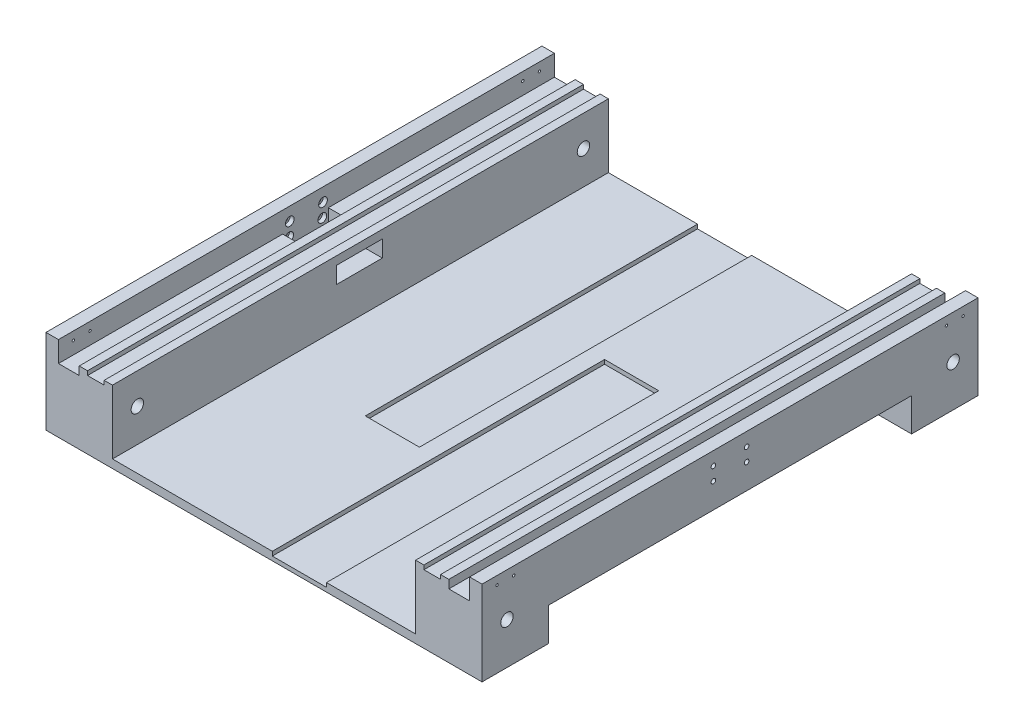
SolidWorks part; units mm, degrees
ref_plane "Front Plane" through (0, 0, 0) normal (0, 0, 1) x (1, 0, 0)
ref_plane "Top Plane" through (0, 0, 0) normal (0, 1, 0) x (1, 0, 0)
ref_plane "Right Plane" through (0, 0, 0) normal (1, 0, 0) x (0, 0, -1)
sketch "Sketch1" plane through (0, 0, 0) normal (0, 0, 1) x (1, 0, 0)
  line L0 (0, 0) -> (0, 95)
  line L1 (0, 95) -> (20, 95)
  line L2 (20, 95) -> (20, 75)
  line L3 (20, 75) -> (40, 75)
  line L4 (40, 75) -> (40, 80)
  line L5 (40, 80) -> (50, 80)
  line L6 (50, 80) -> (50, 75)
  line L7 (50, 75) -> (70, 75)
  line L8 (70, 75) -> (70, 80)
  line L9 (70, 80) -> (80, 80)
  line L10 (80, 80) -> (80, 15)
  line L11 (80, 15) -> (445, 15)
  line L23 (237.9167, 0) -> (0, 0)
  line L24 (262.5, 146.857) -> (262.5, -30.5268)
  line L25 (287.0833, 0) -> (525, 0)
  line L26 (445, 80) -> (445, 15)
  line L27 (455, 80) -> (445, 80)
  line L28 (455, 75) -> (455, 80)
  line L29 (475, 75) -> (455, 75)
  line L30 (485, 80) -> (475, 80)
  line L31 (485, 75) -> (485, 80)
  line L32 (505, 75) -> (485, 75)
  line L33 (505, 95) -> (505, 75)
  line L34 (525, 95) -> (505, 95)
  line L35 (525, 0) -> (525, 95)
  line L36 (475, 75) -> (475, 80)
  line L37 (237.9167, 0) -> (287.0833, 0)
  point P19 (262.5, 15)
  dimension "D1" = 10
  dimension "D2" = 10
  dimension "D3" = 182.5
  dimension "D4" = 20
  dimension "D5" = 20
  dimension "D6" = 20
  dimension "D7" = 20
  dimension "D8" = 5
  dimension "D9" = 5
  dimension "D10" = 65
  dimension "D11" = 80
  dimension "D12" = 95
extrude "Boss-Extrude1" add sketch "Sketch1" along normal blind 597.1 contours L23 L37 L24 L11 L10 L9 L8 L7 L6 L5 L4 L3 L2 L1 L0 | L24 L37 L25 L35 L34 L33 L32 L31 L30 L36 L29 L28 L27 L26 L11
sketch "Sketch2" plane through (0, 15, 0) normal (0, 1, 0) x (1, 0, 0)
  line L0 (80, 0) -> (445, 0) construction
  line L1 (187.3, 0) -> (252.5, 0)
  line L2 (187.3, 0) -> (187.3, -400)
  line L3 (187.3, -400) -> (252.5, -400)
  line L4 (252.5, 0) -> (252.5, -400)
  line L5 (80, -597.1) -> (445, -597.1) construction
  line L6 (272.5, -597.1) -> (337.7, -597.1)
  line L7 (272.5, -597.1) -> (272.5, -197.1)
  line L8 (272.5, -197.1) -> (337.7, -197.1)
  line L9 (337.7, -597.1) -> (337.7, -197.1)
  line L10 (445, -597.1) -> (445, 0) construction
  dimension "D1" = 400
  dimension "D2" = 400
  dimension "D3" = 65.2
  dimension "D4" = 65.2
  dimension "D5" = 20
  dimension "D6" = 107.3
extrude "Cut-Extrude1" cut sketch "Sketch2" against normal through all
sketch "Sketch3" plane through (0, 15, 0) normal (0, 1, 0) x (1, 0, 0)
  line L1 (80, 0) -> (445, 0)
  line L2 (80, 0) -> (80, -597.1)
  line L3 (80, -597.1) -> (445, -597.1)
  line L4 (445, 0) -> (445, -597.1)
  line L5 (187.3, 0) -> (252.5, 0)
  line L6 (187.3, 0) -> (187.3, -400)
  line L7 (187.3, -400) -> (252.5, -400)
  line L8 (252.5, 0) -> (252.5, -400)
  line L9 (272.5, -197.1) -> (337.7, -197.1)
  line L10 (272.5, -197.1) -> (272.5, -597.1)
  line L11 (272.5, -597.1) -> (337.7, -597.1)
  line L12 (337.7, -197.1) -> (337.7, -597.1)
  line M1 (187.3, -400) -> (187.3, 0)
  line M2 (187.3, 0) -> (80, 0)
  line M3 (80, 0) -> (80, -597.1)
  line M4 (80, -597.1) -> (272.5, -597.1)
  line M5 (272.5, -597.1) -> (272.5, -197.1)
  line M6 (272.5, -197.1) -> (337.7, -197.1)
  line M7 (337.7, -197.1) -> (337.7, -597.1)
  line M8 (337.7, -597.1) -> (445, -597.1)
  line M9 (445, -597.1) -> (445, 0)
  line M10 (445, 0) -> (252.5, 0)
  line M11 (252.5, 0) -> (252.5, -400)
  line M12 (252.5, -400) -> (187.3, -400)
extrude "Boss-Extrude2" add sketch "Sketch3" along normal blind 8 contours M12 M1 M2 M3 M4 M5 M6 M7 M8 M9 M10 M11
sketch "Sketch4" plane through (0, 0, 0) normal (0, -1, 0) x (1, 0, 0)
  line L1 (0, 597.1) -> (525, 597.1)
  line L2 (0, 597.1) -> (0, 0)
  line L3 (0, 0) -> (525, 0)
  line L4 (525, 597.1) -> (525, 0)
extrude "Boss-Extrude3" add sketch "Sketch4" along normal blind 7
sketch "Sketch5" plane through (0, 23, 0) normal (0, 1, 0) x (1, 0, 0)
  line L1 (80, 0) -> (445, 0)
  line L2 (80, 0) -> (80, -597.1)
  line L3 (80, -597.1) -> (445, -597.1)
  line L4 (445, 0) -> (445, -597.1)
extrude "Cut-Extrude2" cut sketch "Sketch5" against normal blind 10
sketch "Sketch6" plane through (525, 0, 0) normal (1, 0, 0) x (0, 0, -1)
  line L0 (-597.1, 95) -> (0, 95) construction
  line L1 (-324.55, 95) -> (-272.55, 95)
  line L2 (-324.55, 95) -> (-324.55, 55)
  line L3 (-324.55, 55) -> (-272.55, 55)
  line L4 (-272.55, 95) -> (-272.55, 55)
  line L6 (-597.1, -7) -> (-597.1, 95) construction
  circle A0 centre (-318.55, 79) radius 2.125
  circle A1 centre (-278.55, 79) radius 2.125
  circle A2 centre (-278.55, 63) radius 2.125
  circle A3 centre (-318.55, 63) radius 2.125
  circle A4 centre (-318.55, 79) radius 2.125
  circle A5 centre (-278.55, 79) radius 2.125
  circle A6 centre (-278.55, 63) radius 2.125
  circle A7 centre (-318.55, 63) radius 2.125
  dimension "D4" = 4.25
  dimension "D1" = 52
  dimension "D2" = 40
  dimension "D3" = 272.55
  dimension "D5" = 40
  dimension "D6" = 40
  dimension "D7" = 16
  dimension "D8" = 16
  dimension "D9" = 6
  dimension "D10" = 8
extrude "Cut-Extrude3" cut sketch "Sketch6" against normal up to next contours A0 | A3 | A2 | A1
cosmetic thread "Cosmetic Thread5" parameters "D2"=5.5
cosmetic thread "Cosmetic Thread6" parameters "D2"=5.5
cosmetic thread "Cosmetic Thread7" parameters "D2"=5.5
cosmetic thread "Cosmetic Thread8" parameters "D2"=5.5
sketch "Sketch7" plane through (0, 75, 0) normal (0, 1, 0) x (1, 0, 0)
  line L1 (485, 0) -> (505, 0)
  line L2 (485, 0) -> (485, -597.1)
  line L3 (485, -597.1) -> (505, -597.1)
  line L4 (505, 0) -> (505, -597.1)
extrude "Cut-Extrude4" cut sketch "Sketch7" against normal blind 5
sketch "Sketch8" plane through (445, 0, 0) normal (-1, 0, 0) x (0, 0, 1)
  line L0 (597.1, 80) -> (0, 80) construction
  line L1 (269.8676, 50) -> (324.923, 50)
  line L2 (269.8676, 50) -> (269.8676, 70)
  line L3 (269.8676, 70) -> (324.923, 70)
  line L4 (324.923, 50) -> (324.923, 70)
  dimension "D1" = 20
  dimension "D2" = 55.0555
  dimension "D3" = 10
extrude "Cut-Extrude6" cut sketch "Sketch8" against normal blind 60
sketch "Sketch13" plane through (0, 50, 0) normal (0, 1, 0) x (1, 0, 0)
  line L0 (445, -269.8676) -> (445, -324.923) construction
  line L1 (445, -290.3007) -> (485, -290.3007)
  line L2 (445, -290.3007) -> (445, -305.3007)
  line L3 (445, -305.3007) -> (485, -305.3007)
  line L4 (485, -290.3007) -> (485, -305.3007)
  dimension "D1" = 15
  dimension "D2" = 40
extrude "Boss-Extrude4" add sketch "Sketch13" along normal up to next
sketch "Sketch14" plane through (0, 75, 0) normal (0, 1, 0) x (1, 0, 0)
  line L1 (20, 0) -> (40, 0)
  line L2 (20, 0) -> (20, -597.1)
  line L3 (20, -597.1) -> (40, -597.1)
  line L4 (40, 0) -> (40, -597.1)
extrude "Cut-Extrude7" cut sketch "Sketch14" against normal blind 5
sketch "Sketch15" plane through (0, 0, 0) normal (-1, 0, 0) x (0, 0, 1)
  line L0 (597.1, 95) -> (0, 95) construction
  line L1 (10, 95) -> (37, 95)
  line L2 (10, 95) -> (10, 49.6)
  line L3 (10, 49.6) -> (37, 49.6)
  line L4 (37, 95) -> (37, 49.6)
  line L5 (0, -7) -> (0, 95) construction
  line L10 (298.55, -7) -> (298.55, 95)
  line L11 (597.1, -7) -> (0, -7) construction
  line L12 (587.1, 49.6) -> (560.1, 49.6)
  line L13 (587.1, 95) -> (560.1, 95)
  line L14 (587.1, 95) -> (587.1, 49.6)
  line L15 (560.1, 95) -> (560.1, 49.6)
  circle A0 centre (13.5, 82.3) radius 1.33
  circle A1 centre (33.5, 82.3) radius 1.33
  circle A2 centre (33.5, 62.3) radius 1.33
  circle A3 centre (13.5, 62.3) radius 1.33
  circle A4 centre (563.6, 62.3) radius 1.33
  circle A5 centre (563.6, 82.3) radius 1.33
  circle A6 centre (583.6, 82.3) radius 1.33
  circle A7 centre (583.6, 62.3) radius 1.33
  circle A8 centre (13.5, 82.3) radius 1.33
  circle A9 centre (33.5, 82.3) radius 1.33
  circle A10 centre (33.5, 62.3) radius 1.33
  circle A11 centre (13.5, 62.3) radius 1.33
  dimension "D2" = 2.66
  dimension "D1" = 10
  dimension "D3" = 45.4
  dimension "D4" = 27
  dimension "D5" = 20
  dimension "D6" = 20
  dimension "D7" = 20
  dimension "D8" = 20
  dimension "D9" = 3.5
  dimension "D10" = 12.7
extrude "Cut-Extrude8" cut sketch "Sketch15" against normal up to next contours A0 | A1 | A3 | A2 | A5 | A7 | A4 | A6
cosmetic thread "Cosmetic Thread9" parameters "D2"=3.2
cosmetic thread "Cosmetic Thread10" parameters "D2"=3.2
cosmetic thread "Cosmetic Thread11" parameters "D2"=3.2
cosmetic thread "Cosmetic Thread12" parameters "D2"=3.2
cosmetic thread "Cosmetic Thread13" parameters "D2"=3.2
cosmetic thread "Cosmetic Thread14" parameters "D2"=3.2
cosmetic thread "Cosmetic Thread15" parameters "D2"=3.2
cosmetic thread "Cosmetic Thread16" parameters "D2"=3.2
sketch "Sketch16" plane through (80, 0, 0) normal (1, 0, 0) x (0, 0, -1)
  line L0 (-597.1, 80) -> (-597.1, 13) construction
  line L1 (-592.1, 70) -> (-557.1, 70)
  line L2 (-592.1, 70) -> (-592.1, 55)
  line L3 (-592.1, 55) -> (-557.1, 55)
  line L4 (-557.1, 70) -> (-557.1, 55)
  line L5 (-597.1, 80) -> (0, 80) construction
  line L6 (0, 80) -> (0, 13) construction
  line L7 (-40, 55) -> (-5, 55)
  line L8 (-40, 55) -> (-40, 70)
  line L9 (-40, 70) -> (-5, 70)
  line L10 (-5, 55) -> (-5, 70)
  dimension "D1" = 5
  dimension "D2" = 15
  dimension "D3" = 10
  dimension "D4" = 35
  dimension "D5" = 10
  dimension "D6" = 5
  dimension "D7" = 35
  dimension "D8" = 15
extrude "Cut-Extrude9" cut sketch "Sketch16" against normal blind 60
sketch "Sketch17" plane through (0, -7, 0) normal (0, -1, 0) x (1, 0, 0)
  line L0 (525, 0) -> (525, 597.1) construction
  line L1 (465, 373.55) -> (525, 373.55)
  line L2 (465, 373.55) -> (465, 223.55)
  line L3 (465, 223.55) -> (525, 223.55)
  line L4 (525, 373.55) -> (525, 223.55)
  line L5 (525, 597.1) -> (0, 597.1) construction
  dimension "D1" = 150
  dimension "D2" = 223.55
  dimension "D3" = 60
extrude "Cut-Extrude10" cut sketch "Sketch17" against normal blind 40
sketch "Sketch18" plane through (0, 13, 0) normal (0, 1, 0) x (1, 0, 0)
  line L1 (427, -286.05) -> (415, -286.05)
  line L2 (427, -286.05) -> (427, -302.05)
  line L3 (427, -302.05) -> (415, -302.05)
  line L4 (415, -286.05) -> (415, -302.05)
  line L5 (417, -286.05) -> (425, -286.05)
  line L6 (445, 0) -> (252.5, 0) construction
  line L7 (417, -286.05) -> (417, -279.05)
  line L8 (445, -597.1) -> (445, 0) construction
  line L9 (417, -279.05) -> (425, -279.05)
  line L10 (425, -286.05) -> (425, -279.05)
  line L11 (417, -302.05) -> (425, -302.05)
  line L12 (417, -302.05) -> (417, -309.05)
  line L13 (417, -309.05) -> (425, -309.05)
  line L14 (425, -302.05) -> (425, -309.05)
  dimension "D1" = 12
  dimension "D2" = 16
  dimension "D3" = 286.05
  dimension "D4" = 30
  dimension "D5" = 8
  dimension "D6" = 7
  dimension "D7" = 2
  dimension "D8" = 8
  dimension "D9" = 7
  dimension "D10" = 2
extrude "Cut-Extrude11" cut sketch "Sketch18" against normal through all contours L1 L4 L3 L2
sketch "Sketch19" plane through (0, 13, 0) normal (0, 1, 0) x (1, 0, 0)
  line L0 (427, -286.05) -> (415, -286.05) construction
  line L1 (417, -286.05) -> (425, -286.05)
  line L2 (417, -286.05) -> (417, -279.05)
  line L3 (417, -279.05) -> (425, -279.05)
  line L4 (425, -286.05) -> (425, -279.05)
  line L5 (427, -302.05) -> (415, -302.05) construction
  line L6 (417, -302.05) -> (425, -302.05)
  line L7 (417, -302.05) -> (417, -309.05)
  line L8 (417, -309.05) -> (425, -309.05)
  line L9 (425, -302.05) -> (425, -309.05)
  line L10 (415, -286.05) -> (415, -302.05) construction
  dimension "D1" = 8
  dimension "D2" = 8
  dimension "D3" = 7
  dimension "D4" = 7
  dimension "D5" = 2
  dimension "D6" = 2
extrude "Cut-Extrude12" cut sketch "Sketch19" against normal blind 10
sketch "Sketch20" plane through (525, 0, 0) normal (1, 0, 0) x (0, 0, -1)
  circle A0 centre (-318.55, 79) radius 2.7599
  circle A1 centre (-318.55, 63) radius 2.758
  circle A2 centre (-278.55, 63) radius 2.7761
  circle A3 centre (-278.55, 79) radius 2.7514
extrude "Cut-Extrude13" cut sketch "Sketch20" against normal up to next
sketch "Sketch21" plane through (0, 0, 0) normal (-1, 0, 0) x (0, 0, 1)
  circle A0 centre (13.5, 82.3) radius 1.6434
  circle A1 centre (13.5, 62.3) radius 1.6389
  circle A2 centre (33.5, 62.3) radius 1.6445
  circle A3 centre (33.5, 82.3) radius 1.706
  circle A4 centre (563.6, 62.3) radius 1.6454
  circle A5 centre (583.6, 62.3) radius 1.6466
  circle A6 centre (583.6, 82.3) radius 1.6613
  circle A7 centre (563.6, 82.3) radius 1.7012
extrude "Cut-Extrude14" cut sketch "Sketch21" against normal up to next
sketch "Sketch22" plane through (445, 0, 0) normal (-1, 0, 0) x (0, 0, 1)
  line L1 (290.3007, 70) -> (305.3007, 70)
  line L2 (290.3007, 70) -> (290.3007, 50)
  line L3 (290.3007, 50) -> (305.3007, 50)
  line L4 (305.3007, 70) -> (305.3007, 50)
extrude "Cut-Extrude15" cut sketch "Sketch22" against normal up to next
sketch "Sketch24" plane through (525, 0, 0) normal (1, 0, 0) x (0, 0, -1)
  line L0 (-597.1, -7) -> (-597.1, 95) construction
  line L1 (-597.1, 95) -> (0, 95) construction
  line L4 (0, -7) -> (0, 95) construction
  circle A0 centre (-583.6, 82.3) radius 1.5
  circle A1 centre (-563.6, 82.3) radius 1.5
  circle A2 centre (-583.6, 62.3) radius 1.5
  circle A3 centre (-563.6, 62.3) radius 1.5
  circle A4 centre (-33.5, 82.3) radius 1.5
  circle A5 centre (-13.5, 82.3) radius 1.5
  circle A6 centre (-13.5, 62.3) radius 1.5
  circle A7 centre (-33.5, 62.3) radius 1.5
  dimension "D1" = 3
  dimension "D2" = 13.5
  dimension "D3" = 12.7
  dimension "D4" = 20
  dimension "D5" = 13.5
  dimension "D6" = 12.7
  dimension "D7" = 20
  dimension "D8" = 20
  dimension "D9" = 20
  dimension "D10" = 13.5
  dimension "D11" = 20
  dimension "D12" = 20
  dimension "D13" = 20
  dimension "D14" = 20
  dimension "D15" = 12.7
  dimension "D16" = 13.5
  dimension "D17" = 12.7
extrude "Cut-Extrude16" cut sketch "Sketch24" against normal up to next
sketch "Sketch27" plane through (445, 0, 0) normal (-1, 0, 0) x (0, 0, 1)
  line L0 (597.1, 80) -> (0, 80) construction
  line L1 (592.1, 70) -> (557.1, 70)
  line L2 (592.1, 70) -> (592.1, 55)
  line L3 (592.1, 55) -> (557.1, 55)
  line L4 (557.1, 70) -> (557.1, 55)
  line L5 (597.1, 80) -> (597.1, 13) construction
  dimension "D1" = 10
  dimension "D2" = 5
  dimension "D3" = 35
  dimension "D4" = 15
extrude "Cut-Extrude17" cut sketch "Sketch27" against normal blind 60
sketch "Sketch28" plane through (445, 0, 0) normal (-1, 0, 0) x (0, 0, 1)
  line L1 (0, 80) -> (40, 80)
  line L2 (0, 80) -> (0, 55)
  line L3 (0, 55) -> (40, 55)
  line L4 (40, 80) -> (40, 55)
  line L5 (40, 55) -> (5, 55)
  line L6 (40, 55) -> (40, 70)
  line L7 (40, 70) -> (5, 70)
  line L8 (5, 55) -> (5, 70)
  circle M9 centre (13.5, 62.3) radius 1.5
  circle M10 centre (33.5, 62.3) radius 1.5
  dimension "D1" = 40
  dimension "D2" = 25
  dimension "D3" = 15
  dimension "D4" = 35
extrude "Cut-Extrude18" cut sketch "Sketch28" against normal blind 60 contours L8 L3 L4 L7 M10 M9
sketch "Sketch29" plane through (0, -7, 0) normal (0, -1, 0) x (1, 0, 0)
  line L0 (0, 597.1) -> (0, 0) construction
  line L1 (0, 373.55) -> (60, 373.55)
  line L2 (0, 373.55) -> (0, 223.55)
  line L3 (0, 223.55) -> (60, 223.55)
  line L4 (60, 373.55) -> (60, 223.55)
  dimension "D1" = 60
  dimension "D2" = 150
extrude "Cut-Extrude19" cut sketch "Sketch29" against normal blind 40
sketch "Sketch33" plane through (0, 0, 0) normal (-1, 0, 0) x (0, 0, 1)
  line L0 (597.1, 95) -> (0, 95) construction
  line L1 (597.1, -7) -> (597.1, 95) construction
  circle A0 centre (318.55, 79) radius 2.5
  circle A1 centre (319.3565, 63) radius 2.5
  circle A2 centre (278.55, 79) radius 2.5
  circle A3 centre (279.3565, 63) radius 2.5
  dimension "D1" = 5
  dimension "D2" = 40
  dimension "D3" = 16
  dimension "D4" = 40
  dimension "D5" = 16
  dimension "D6" = 16
  dimension "D7" = 278.55
extrude "Cut-Extrude20" cut sketch "Sketch33" against normal up to next
sketch "Sketch37" plane through (80, 0, 0) normal (1, 0, 0) x (0, 0, -1)
  line L0 (-597.1, 80) -> (0, 80) construction
  line L1 (-327.18, 50) -> (-272.18, 50)
  line L2 (-327.18, 50) -> (-327.18, 70)
  line L3 (-327.18, 70) -> (-272.18, 70)
  line L4 (-272.18, 50) -> (-272.18, 70)
  line L5 (0, 80) -> (0, 13) construction
  dimension "D1" = 20
  dimension "D2" = 55
  dimension "D3" = 10
  dimension "D4" = 272.18
extrude "Cut-Extrude21" cut sketch "Sketch37" against normal blind 60
sketch "Sketch39" plane through (0, 0, 0) normal (-1, 0, 0) x (0, 0, 1)
  line L0 (597.1, 95) -> (0, 95) construction
  line L1 (3, 95) -> (8, 95)
  line L2 (3, 95) -> (3, 55)
  line L3 (3, 55) -> (8, 55)
  line L4 (8, 95) -> (8, 55)
  line L5 (0, -7) -> (0, 95) construction
  line L6 (597.1, -7) -> (597.1, 95) construction
  line L7 (589.1, 95) -> (594.1, 95)
  line L8 (589.1, 95) -> (589.1, 55)
  line L9 (589.1, 55) -> (594.1, 55)
  line L10 (594.1, 95) -> (594.1, 55)
  dimension "D1" = 3
  dimension "D2" = 5
  dimension "D3" = 40
  dimension "D4" = 3
  dimension "D5" = 5
  dimension "D6" = 40
extrude "Boss-Extrude6" add sketch "Sketch39" along normal blind 40
sketch "Sketch41" plane through (0, 0, 3) normal (0, 0, -1) x (-1, 0, 0)
  line L0 (40, 95) -> (0, 95) construction
  line L1 (40, 95) -> (40, 55) construction
  circle A0 centre (10, 85) radius 1.5
  circle A1 centre (30, 85) radius 1.5
  circle A2 centre (30, 65) radius 1.5
  circle A3 centre (10, 65) radius 1.5
  dimension "D1" = 3
  dimension "D2" = 20
  dimension "D3" = 20
  dimension "D4" = 20
  dimension "D5" = 20
  dimension "D6" = 10
  dimension "D7" = 10
  dimension "D8" = 10
extrude "Cut-Extrude22" cut sketch "Sketch41" against normal through all
sketch "Sketch42" plane through (80, 0, 0) normal (1, 0, 0) x (0, 0, -1)
  line L1 (-592.1, 70) -> (-557.1, 70)
  line L2 (-592.1, 70) -> (-592.1, 55)
  line L3 (-592.1, 55) -> (-557.1, 55)
  line L4 (-557.1, 70) -> (-557.1, 55)
  line L5 (-40, 70) -> (-5, 70)
  line L6 (-40, 70) -> (-40, 55)
  line L7 (-40, 55) -> (-5, 55)
  line L8 (-5, 70) -> (-5, 55)
extrude "Boss-Extrude7" add sketch "Sketch42" against normal blind 60
sketch "Sketch43" plane through (0, 0, 0) normal (-1, 0, 0) x (0, 0, 1)
  line L0 (589.1, 95) -> (8, 95) construction
  line L1 (8, 95) -> (49.1479, 95)
  line L2 (8, 95) -> (8, 53.381)
  line L3 (8, 53.381) -> (49.1479, 53.381)
  line L4 (49.1479, 95) -> (49.1479, 53.381)
  line L5 (546.6637, 95) -> (589.1, 95)
  line L6 (546.6637, 95) -> (546.6637, 55)
  line L7 (546.6637, 55) -> (589.1, 55)
  line L8 (589.1, 95) -> (589.1, 55)
extrude "Boss-Extrude8" add sketch "Sketch43" against normal blind 20
sketch "Sketch44" plane through (525, 0, 0) normal (1, 0, 0) x (0, 0, -1)
  line L0 (-597.1, 95) -> (0, 95) construction
  line L1 (-597.1, 95) -> (-547.4631, 95)
  line L2 (-597.1, 95) -> (-597.1, 48.775)
  line L3 (-597.1, 48.775) -> (-547.4631, 48.775)
  line L4 (-547.4631, 95) -> (-547.4631, 48.775)
  line L5 (-1.3119, 95) -> (-48.1855, 95)
  line L6 (-1.3119, 95) -> (-1.3119, 48.775)
  line L7 (-1.3119, 48.775) -> (-48.1855, 48.775)
  line L8 (-48.1855, 95) -> (-48.1855, 48.775)
extrude "Boss-Extrude9" add sketch "Sketch44" against normal blind 20
sketch "Sketch45" plane through (445, 0, 0) normal (-1, 0, 0) x (0, 0, 1)
  line L1 (5, 70) -> (40, 70)
  line L2 (5, 70) -> (5, 55)
  line L3 (5, 55) -> (40, 55)
  line L4 (40, 70) -> (40, 55)
  line L5 (557.1, 70) -> (592.1, 70)
  line L6 (557.1, 70) -> (557.1, 55)
  line L7 (557.1, 55) -> (592.1, 55)
  line L8 (592.1, 70) -> (592.1, 55)
extrude "Boss-Extrude10" add sketch "Sketch45" against normal blind 60
sketch "Sketch46" plane through (525, 0, 0) normal (1, 0, 0) x (0, 0, -1)
  line L0 (-597.1, 95) -> (0, 95) construction
  line L1 (-594.1, 95) -> (-589.1, 95)
  line L2 (-594.1, 95) -> (-594.1, 55)
  line L3 (-594.1, 55) -> (-589.1, 55)
  line L4 (-589.1, 95) -> (-589.1, 55)
  line L5 (-597.1, -7) -> (-597.1, 95) construction
  line L6 (0, -7) -> (0, 95) construction
  line L7 (-8, 95) -> (-3, 95)
  line L8 (-8, 95) -> (-8, 55)
  line L9 (-8, 55) -> (-3, 55)
  line L10 (-3, 95) -> (-3, 55)
  dimension "D1" = 5
  dimension "D2" = 40
  dimension "D3" = 3
  dimension "D4" = 5
  dimension "D5" = 3
  dimension "D6" = 40
extrude "Boss-Extrude11" add sketch "Sketch46" along normal blind 40
sketch "Sketch47" plane through (0, 0, 3) normal (0, 0, -1) x (-1, 0, 0)
  line L0 (-565, 95) -> (-525, 95) construction
  line L1 (-565, 55) -> (-565, 95) construction
  circle A0 centre (-555, 85) radius 1.5
  circle A1 centre (-535, 84.6583) radius 1.5
  circle A2 centre (-535, 64.6583) radius 1.5
  circle A3 centre (-555, 65) radius 1.5
  dimension "D7" = 3
  dimension "D1" = 10
  dimension "D2" = 10
  dimension "D3" = 20
  dimension "D4" = 20
  dimension "D5" = 20
  dimension "D6" = 20
  dimension "D8" = 10
extrude "Cut-Extrude23" cut sketch "Sketch47" against normal through all
ref_plane "Plane2" through (525, 95, 589.1) normal (0, 1, 0) x (1, 0, 0)
fillet "Fillet1" radius 5 1 edges at (0, 75, 8)
fillet "Fillet2" radius 5 3 edges at (525, 75, 8) (525, 75, 589.1) (0, 75, 589.1)
ref_plane "Plane3" through (525, -7, 223.55) normal (0, -1, 0) x (-1, 0, 0)
sketch "Sketch50" plane through (525, -7, 223.55) normal (0, -1, 0) x (1, 0, 0)
  line L10 (-525, 373.55) -> (-525, 150) construction
  line L11 (-525, 293.55) -> (-465, 293.55)
  line L12 (-525, 293.55) -> (-525, -143.55)
  line L13 (-525, -143.55) -> (-465, -143.55)
  line L14 (-465, 293.55) -> (-465, -143.55)
  line L15 (0, 150) -> (0, 373.55) construction
  line L16 (0, 293.55) -> (-60, 293.55)
  line L17 (0, 293.55) -> (0, -143.55)
  line L18 (0, -143.55) -> (-60, -143.55)
  line L19 (-60, 293.55) -> (-60, -143.55)
  line L21 (0, 373.55) -> (-525, 373.55) construction
  line L22 (-525, -223.55) -> (0, -223.55) construction
  dimension "D1" = 60
  dimension "D2" = 60
  dimension "D3" = 80
  dimension "D4" = 80
  dimension "D5" = 80
  dimension "D6" = 80
extrude "Cut-Extrude25" cut sketch "Sketch50" against normal blind 40
sketch "Sketch51" plane through (0, 0, 0) normal (-1, 0, 0) x (0, 0, 1)
  line L0 (584.1, 95) -> (13, 95) construction
  line L1 (48, 95) -> (8, 95)
  line L2 (48, 95) -> (48, 55)
  line L3 (48, 55) -> (8, 55)
  line L4 (8, 95) -> (8, 55)
  line L5 (8, 55) -> (8, 95) construction
  line L6 (8, 55) -> (8, 95) construction
  dimension "D1" = 40
extrude "Boss-Extrude12" add sketch "Sketch51" along normal blind 5
sketch "Sketch52" plane through (-5, 0, 0) normal (-1, 0, 0) x (0, 0, 1)
  line L0 (8, 55) -> (8, 95) construction
  line L1 (48, 95) -> (8, 95) construction
  circle A0 centre (18, 85) radius 3
  circle A1 centre (28, 85) radius 3
  circle A2 centre (38, 85) radius 3
  dimension "D1" = 6
  dimension "D2" = 10
  dimension "D3" = 10
  dimension "D4" = 10
  dimension "D5" = 10
extrude "Cut-Extrude26" cut sketch "Sketch52" against normal through all
sketch "Sketch53" plane through (-5, 0, 0) normal (-1, 0, 0) x (0, 0, 1)
  circle A0 centre (28, 85) radius 3.2804
extrude "Boss-Extrude13" add sketch "Sketch53" against normal through all
sketch "Sketch54" plane through (565, 0, 0) normal (1, 0, 0) x (0, 0, -1)
  circle A0 centre (-28, 85) radius 3.2804
extrude "Cut-Extrude27" cut sketch "Sketch54" against normal blind 40
sketch "Sketch55" plane through (0, 0, 0) normal (0, 0, -1) x (-1, 0, 0)
  line L0 (-20, 95) -> (-20, 70) construction
  line L1 (-505, 95) -> (-20, 95)
  line L2 (-505, 95) -> (-505, 80.5212)
  line L3 (-505, 80.5212) -> (-20, 80.5212)
  line L4 (-20, 95) -> (-20, 80.5212)
extrude "Cut-Extrude28" cut sketch "Sketch55" against normal blind 40
sketch "Sketch56" plane through (525, 0, 0) normal (1, 0, 0) x (0, 0, -1)
  line L2 (-578.1, 95) -> (-600.1, 95) construction
  line L3 (-597.1, -7) -> (-597.1, 95) construction
  circle A0 centre (-579.1, 85) radius 3
  circle A1 centre (-559.1, 85) radius 3
  dimension "D1" = 6
  dimension "D2" = 6
  dimension "D3" = 10
  dimension "D4" = 18
  dimension "D5" = 20
  dimension "D6" = 10
extrude "Cut-Extrude29" cut sketch "Sketch56" against normal through all
sketch "Sketch57" plane through (0, 0, 0) normal (0, 0, -1) x (-1, 0, 0)
  line L1 (0, 95) -> (152.8383, 95)
  line L2 (0, 95) -> (0, 17.2955)
  line L3 (0, 17.2955) -> (152.8383, 17.2955)
  line L4 (152.8383, 95) -> (152.8383, 17.2955)
  line L5 (-525, 95) -> (-626.7109, 95)
  line L6 (-525, 95) -> (-525, 17.2955)
  line L7 (-525, 17.2955) -> (-626.7109, 17.2955)
  line L8 (-626.7109, 95) -> (-626.7109, 17.2955)
extrude "Cut-Extrude30" cut sketch "Sketch57" against normal through all
sketch "Sketch58" plane through (20, 0, 0) normal (1, 0, 0) x (0, 0, -1)
  circle A0 centre (-318.55, 79) radius 5.25
  circle A1 centre (-278.55, 79) radius 5.25
  dimension "D1" = 10.5
  dimension "D2" = 10.5
extrude "Cut-Extrude31" cut sketch "Sketch58" against normal blind 10
sketch "Sketch59" plane through (20, 0, 0) normal (1, 0, 0) x (0, 0, -1)
  circle A0 centre (-319.3565, 63) radius 5.25
  circle A1 centre (-279.3565, 63) radius 5.25
  dimension "D1" = 10.5
  dimension "D2" = 10.5
extrude "Cut-Extrude32" cut sketch "Sketch59" against normal blind 10
sketch "Sketch60" plane through (505, 0, 0) normal (-1, 0, 0) x (0, 0, 1)
  circle A0 centre (278.55, 79) radius 5.25
  circle A1 centre (318.55, 79) radius 5.25
  circle A2 centre (318.55, 63) radius 5.25
  circle A3 centre (278.55, 63) radius 5.25
  dimension "D1" = 10.5
extrude "Cut-Extrude33" cut sketch "Sketch60" against normal blind 10
sketch "Sketch62" plane through (0, 0, 0) normal (-1, 0, 0) x (0, 0, 1)
  circle A0 centre (18, 85) radius 1.5
  circle A1 centre (38, 85) radius 1.5
  circle A2 centre (559.1, 85) radius 1.5
  circle A3 centre (579.1, 85) radius 1.5
  circle A4 centre (18, 85) radius 3.5
  circle A5 centre (38, 85) radius 3.5
  circle A6 centre (559.1, 85) radius 3.5
  circle A7 centre (579.1, 85) radius 3.5
  dimension "D1" = 3
  dimension "D2" = 7
extrude "Boss-Extrude15" add sketch "Sketch62" against normal blind 20
sketch "Sketch64" plane through (525, 0, 0) normal (1, 0, 0) x (0, 0, -1)
  circle A0 centre (-579.1, 85) radius 3.5
  circle A1 centre (-559.1, 85) radius 3.5
  circle A2 centre (-18, 85) radius 3.5
  circle A3 centre (-38, 85) radius 3.5
  circle A4 centre (-38, 85) radius 1.5
  circle A5 centre (-18, 85) radius 1.5
  circle A6 centre (-579.1, 85) radius 1.5
  circle A7 centre (-559.1, 85) radius 1.5
  dimension "D1" = 3
  dimension "D2" = 7
extrude "Boss-Extrude16" add sketch "Sketch64" against normal blind 20
sketch "Sketch65" plane through (0, 0, 0) normal (0, 0, -1) x (-1, 0, 0)
  line L1 (-505, 95) -> (-510, 95)
  line L2 (-505, 95) -> (-505, 70)
  line L3 (-505, 70) -> (-510, 70)
  line L4 (-510, 95) -> (-510, 70)
  line L5 (-20, 95) -> (-15, 95)
  line L6 (-20, 95) -> (-20, 70)
  line L7 (-20, 70) -> (-15, 70)
  line L8 (-15, 95) -> (-15, 70)
  dimension "D1" = 5
  dimension "D2" = 5
extrude "Cut-Extrude34" cut sketch "Sketch65" against normal through all
sketch "Sketch66" plane through (0, 70, 0) normal (0, 1, 0) x (1, 0, 0)
  line L0 (15, -597.1) -> (15, 0) construction
  line L1 (20, -272.18) -> (15, -272.18)
  line L2 (20, -272.18) -> (20, -327.18)
  line L3 (20, -327.18) -> (15, -327.18)
  line L4 (15, -272.18) -> (15, -327.18)
  line L5 (510, -597.1) -> (510, 0) construction
  line L6 (505, -269.8676) -> (510, -269.8676)
  line L7 (505, -269.8676) -> (505, -324.9004)
  line L8 (505, -324.9004) -> (510, -324.9004)
  line L9 (510, -269.8676) -> (510, -324.9004)
extrude "Cut-Extrude35" cut sketch "Sketch66" against normal blind 20
sketch "Sketch69" plane through (0, 13, 0) normal (0, 1, 0) x (1, 0, 0)
  line L1 (80, 0) -> (445, 0)
  line L2 (80, 0) -> (80, -597.1)
  line L3 (80, -597.1) -> (445, -597.1)
  line L4 (445, 0) -> (445, -597.1)
extrude "Cut-Extrude36" cut sketch "Sketch69" against normal blind 5
sketch "Sketch70" plane through (0, 0, 0) normal (0, 1, 0) x (1, 0, 0)
  line L1 (187.3, 0) -> (252.5, 0)
  line L2 (187.3, 0) -> (187.3, -400)
  line L3 (187.3, -400) -> (252.5, -400)
  line L4 (252.5, 0) -> (252.5, -400)
  line L5 (272.5, -197.1) -> (337.7, -197.1)
  line L6 (272.5, -197.1) -> (272.5, -597.1)
  line L7 (272.5, -597.1) -> (337.7, -597.1)
  line L8 (337.7, -197.1) -> (337.7, -597.1)
extrude "Cut-Extrude37" cut sketch "Sketch70" against normal blind 2
sketch "Sketch72" plane through (0, 8, 0) normal (0, 1, 0) x (1, 0, 0)
  line L1 (80, 0) -> (445, 0)
  line L2 (80, 0) -> (80, -597.1)
  line L3 (80, -597.1) -> (445, -597.1)
  line L4 (445, 0) -> (445, -597.1)
extrude "Cut-Extrude38" cut sketch "Sketch72" against normal blind 5
sketch "Sketch73" plane through (0, 3, 0) normal (0, 1, 0) x (1, 0, 0)
  line L0 (415, -286.05) -> (427, -286.05) construction
  line L1 (417, -286.05) -> (425, -286.05)
  line L2 (417, -286.05) -> (417, -281.05)
  line L3 (417, -281.05) -> (425, -281.05)
  line L4 (425, -286.05) -> (425, -281.05)
  line L5 (427, -302.05) -> (415, -302.05) construction
  line L6 (417, -302.05) -> (425, -302.05)
  line L7 (417, -302.05) -> (417, -307.05)
  line L8 (417, -307.05) -> (425, -307.05)
  line L9 (425, -302.05) -> (425, -307.05)
  line L10 (427, -302.05) -> (427, -286.05) construction
  dimension "D1" = 5
  dimension "D2" = 8
  dimension "D3" = 2
  dimension "D4" = 8
  dimension "D5" = 5
  dimension "D6" = 2
extrude "Cut-Extrude39" cut sketch "Sketch73" against normal blind 5
sketch "Sketch75" plane through (0, 0, 0) normal (-1, 0, 0) x (0, 0, 1)
  circle A0 centre (30, 43) radius 7.5
  circle A2 centre (567.1, 43) radius 7.5
  dimension "D1" = 15
extrude "Cut-Extrude41" cut sketch "Sketch75" against normal through all
